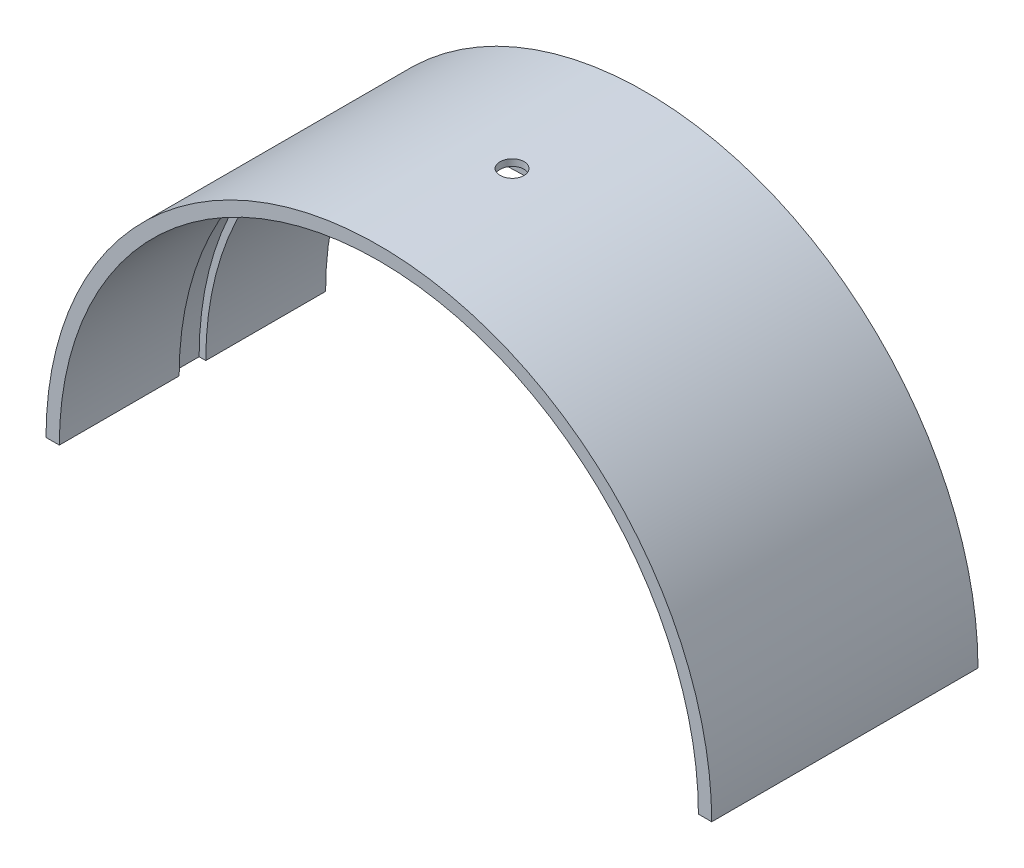
SolidWorks part; units mm, degrees
material "Brass"
ref_plane "Front Plane" through (0, 0, 0) normal (0, 0, 1) x (1, 0, 0)
ref_plane "Top Plane" through (0, 0, 0) normal (0, 1, 0) x (1, 0, 0)
ref_plane "Right Plane" through (0, 0, 0) normal (1, 0, 0) x (0, 0, -1)
sketch "Sketch1" plane through (0, 0, 0) normal (0, 1, 0) x (1, 0, 0)
  line L0 (25, 10) -> (25, -10)
  line L1 (25, -10) -> (24, -10)
  line L4 (24, -10) -> (24, 10)
  line L7 (24, 10) -> (25, 10)
  line L8 (0, 11.5258) -> (0, -8.613) construction
  line L9 (25, 0) -> (0, 0) construction
  line L11 (24, -1) -> (24.5, -1)
  line L12 (24, -1) -> (24, 1)
  line L13 (24, 1) -> (24.5, 1)
  line L14 (24.5, -1) -> (24.5, 1)
  point P2 (25, 0)
  point P14 (0, 0)
  point P16 (24.5, 0)
  dimension "D1" = 50
  dimension "D2" = 2
  dimension "D3" = 1
  dimension "D4" = 0.5
  dimension "D5" = 20
revolve "Revolve1" add sketch "Sketch1" angle 180 about L8
sketch "Sketch2" plane through (0, 0, 0) normal (0, 1, 0) x (1, 0, 0)
  circle A0 centre (0, 0) radius 0.9
  dimension "D1" = 1.8
extrude "Cut-Extrude2" cut sketch "Sketch2" along normal through all
